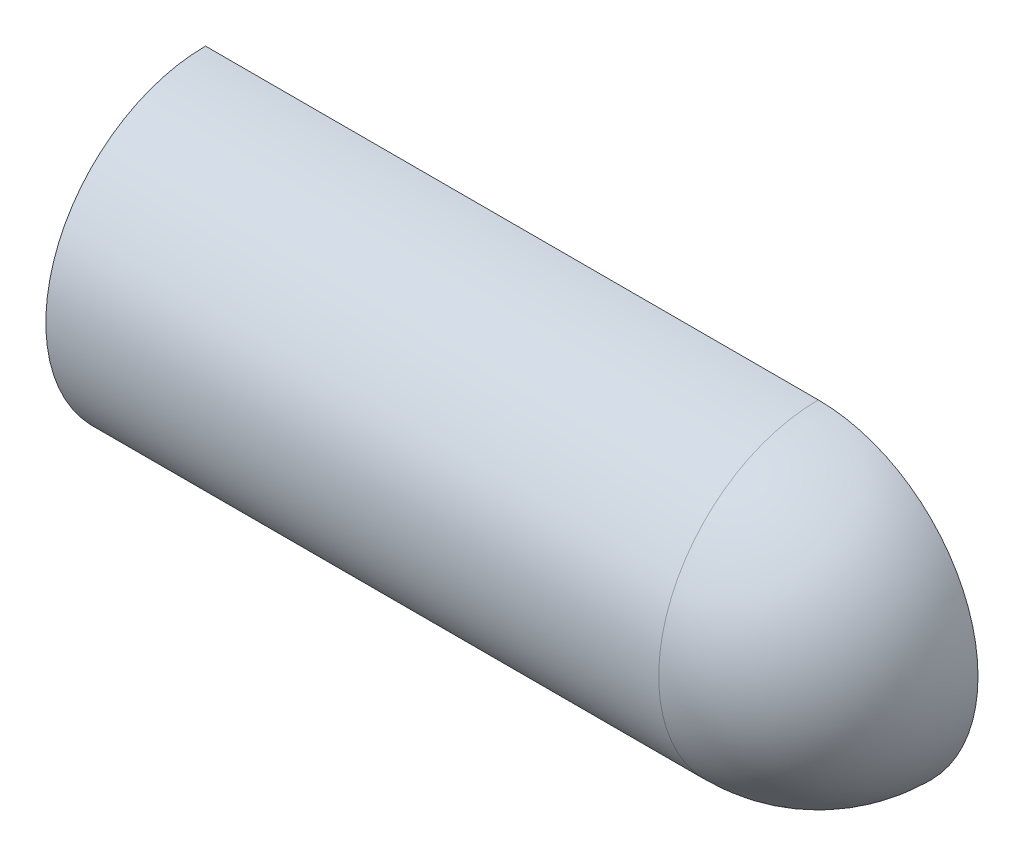
SolidWorks part; units mm, degrees
ref_plane "Front Plane" through (0, 0, 0) normal (0, 0, 1) x (1, 0, 0)
ref_plane "Top Plane" through (0, 0, 0) normal (0, 1, 0) x (1, 0, 0)
ref_plane "Right Plane" through (0, 0, 0) normal (1, 0, 0) x (0, 0, -1)
sketch "Sketch2" plane through (0, 0, 0) normal (0, 0, 1) x (1, 0, 0)
  line L0 (26, 0) -> (31, 0)
  line L2 (-119, 31) -> (0, 31)
  line L3 (-119, 31) -> (-119, 26)
  line L4 (0, 26) -> (-119, 26)
  arc A0 (15.9716, -26.5689) -> (-15.9716, 26.5689) centre (0, 0) ccw construction
  circle A1 centre (0, 0) radius 31 construction
  arc A3 (31, 0) -> (0, 31) centre (0, 0) ccw
  arc A4 (26, 0) -> (0, 26) centre (0, 0) ccw
revolve "Revolve1" add sketch "Sketch2" angle 180 about L0
